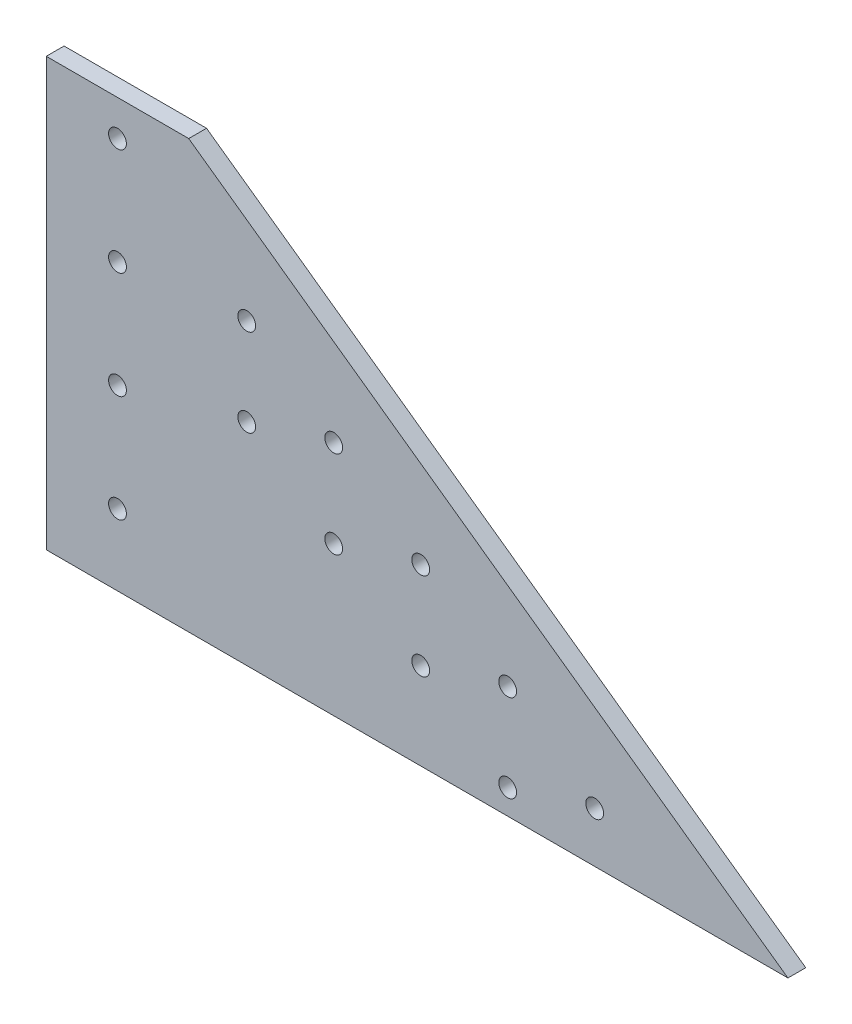
SolidWorks part; units mm, degrees
ref_plane "Front Plane" through (0, 0, 0) normal (0, 0, 1) x (1, 0, 0)
ref_plane "Top Plane" through (0, 0, 0) normal (0, 1, 0) x (1, 0, 0)
ref_plane "Right Plane" through (0, 0, 0) normal (1, 0, 0) x (0, 0, -1)
sketch "Sketch1" plane through (0, 0, 0) normal (0, 0, 1) x (1, 0, 0)
  line L0 (0, 0) -> (25.4, 0)
  line L1 (25.4, 0) -> (132.2285, -76.2)
  line L2 (0, 0) -> (0, -76.2)
  line L3 (132.2285, -76.2) -> (0, -76.2)
  dimension "D1" = 25.4
  dimension "D2" = 76.2
  dimension "D3" = 54.5
extrude "Boss-Extrude1" add sketch "Sketch1" along normal blind 3.175
sketch "Sketch2" plane through (0, 0, 3.175) normal (0, 0, 1) x (1, 0, 0)
  line L0 (12.7, 0) -> (12.7, -6.35) construction
  line L1 (25.4, 0) -> (0, 0) construction
  line L3 (35.7393, -22.9747) -> (35.7393, -57.8287) construction
  line L4 (25.4, 0) -> (25.4, -76.2) construction
  line L5 (124.8535, -86.5393) -> (18.0251, -10.3393)
  line L6 (35.7393, -22.9747) -> (25.4, -15.5998) construction
  line L7 (0, -76.2) -> (132.2285, -76.2) construction
  line L8 (117.4786, -96.8785) -> (10.6501, -20.6785)
  line L9 (62.5925, -57.7286) -> (35.7393, -38.5744) construction
  circle A0 centre (12.7, -6.35) radius 1.5875
  circle A1 centre (12.7, -25.4) radius 1.5875
  circle A2 centre (12.7, -44.45) radius 1.5875
  circle A3 centre (12.7, -63.5) radius 1.5875
  circle A4 centre (35.7393, -22.9747) radius 1.5875
  circle A5 centre (51.2482, -34.0371) radius 1.5875
  circle A6 centre (66.7571, -45.0995) radius 1.5875
  circle A7 centre (82.266, -56.1619) radius 1.5875
  circle A8 centre (97.7749, -67.2242) radius 1.5875
  circle A9 centre (35.7393, -38.5744) radius 1.5875
  circle A10 centre (51.2482, -49.6368) radius 1.5875
  circle A11 centre (66.7571, -60.6992) radius 1.5875
  circle A12 centre (82.266, -71.7616) radius 1.5875
  dimension "D2" = 3.175
  dimension "D6" = 3.175
  dimension "D9" = 3.175
  dimension "D1" = 6.35
  dimension "D5" = 12.7
  dimension "D4" = 12.7
  dimension "D8" = 25.4
  dimension "D3" = 4
  dimension "D7" = 5
  dimension "D10" = 4
extrude "Cut-Extrude1" cut sketch "Sketch2" against normal up to next
